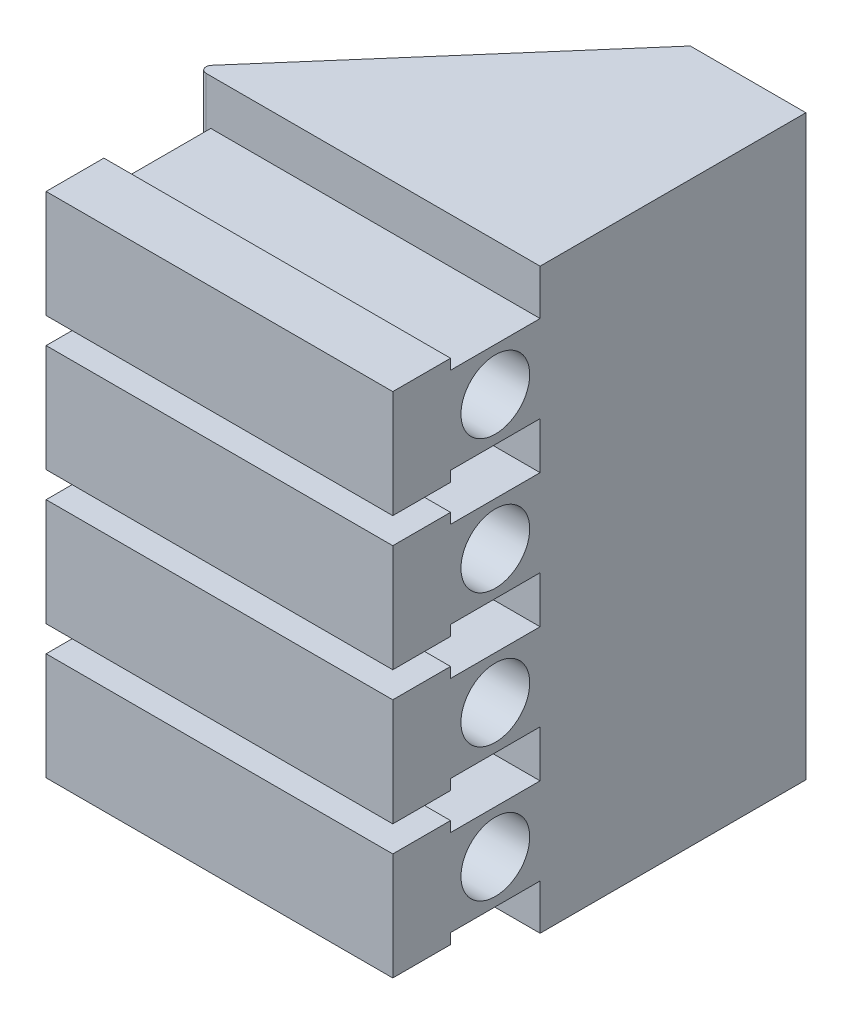
SolidWorks part; units mm, degrees
ref_plane "Front Plane" through (0, 0, 0) normal (0, 0, 1) x (1, 0, 0)
ref_plane "Top Plane" through (0, 0, 0) normal (0, 1, 0) x (1, 0, 0)
ref_plane "Right Plane" through (0, 0, 0) normal (1, 0, 0) x (0, 0, -1)
sketch "Sketch1" plane through (0, 0, 0) normal (0, 1, 0) x (1, 0, 0)
  line L0 (-17.3516, 20.3127) -> (-57.3516, -25.689)
  line L1 (-17.3516, 20.3127) -> (2.6484, 20.3127)
  line L2 (-17.3516, 20.3127) -> (-17.3516, -25.689)
  line L3 (-17.3516, -25.689) -> (2.6484, -25.689)
  line L4 (2.6484, 20.3127) -> (2.6484, -25.689)
  line L5 (-57.3516, -25.689) -> (-17.3516, -25.689)
  dimension "D1" = 20
  dimension "D2" = 40
extrude "Boss-Extrude1" add sketch "Sketch1" against normal blind 100 contours L0 L5 L2 | L4 L1 L2 L3
sketch "Sketch8" plane through (2.6484, 0, 0) normal (1, 0, 0) x (0, 0, -1)
  line L0 (-25.689, -100) -> (-25.689, 0) construction
  line L1 (-25.689, -7.85) -> (-41.189, -7.85)
  line L2 (-25.689, -7.85) -> (-25.689, -22.85)
  line L3 (-25.689, -22.85) -> (-41.189, -22.85)
  line L4 (-41.189, -7.85) -> (-41.189, -22.85)
  line L6 (-25.689, -30.95) -> (-41.189, -30.95)
  line L7 (-25.689, -30.95) -> (-25.689, -45.95)
  line L8 (-25.689, -45.95) -> (-41.189, -45.95)
  line L9 (-41.189, -30.95) -> (-41.189, -45.95)
  line L10 (-25.689, -54.05) -> (-41.189, -54.05)
  line L11 (-25.689, -54.05) -> (-25.689, -69.05)
  line L12 (-25.689, -69.05) -> (-41.189, -69.05)
  line L13 (-41.189, -54.05) -> (-41.189, -69.05)
  line L14 (-25.689, -77.15) -> (-41.189, -77.15)
  line L15 (-25.689, -77.15) -> (-25.689, -92.15)
  line L16 (-25.689, -92.15) -> (-41.189, -92.15)
  line L17 (-41.189, -77.15) -> (-41.189, -92.15)
  dimension "D1" = 7.85
  dimension "D2" = 15
  dimension "D3" = 15.5
  dimension "D4" = 8.1
  dimension "D5" = 8.1
  dimension "D6" = 8.1
  dimension "D7" = 7.85
  dimension "D8" = 15
  dimension "D9" = 15
  dimension "D10" = 15.5
  dimension "D11" = 15.5
  dimension "D12" = 15.5
extrude "Boss-Extrude2" add sketch "Sketch8" against normal blind 57
sketch "Sketch10" plane through (2.6484, 0, 0) normal (1, 0, 0) x (0, 0, -1)
  line L0 (-41.189, -7.85) -> (-41.189, -22.85) construction
  line L1 (-41.189, -22.85) -> (-25.689, -22.85) construction
  line L2 (-41.189, -30.95) -> (-41.189, -45.95) construction
  line L3 (-41.189, -45.95) -> (-25.689, -45.95) construction
  line L4 (-41.189, -54.05) -> (-41.189, -69.05) construction
  line L5 (-41.189, -69.05) -> (-25.689, -69.05) construction
  line L6 (-41.189, -77.15) -> (-41.189, -92.15) construction
  line L7 (-41.189, -92.15) -> (-25.689, -92.15) construction
  circle A0 centre (-33.439, -15.35) radius 5.95
  circle A1 centre (-33.439, -38.45) radius 5.95
  circle A2 centre (-33.439, -61.55) radius 5.95
  circle A3 centre (-33.439, -84.65) radius 5.95
  dimension "D1" = 11.9
  dimension "D2" = 11.9
  dimension "11.9" = 11.9
  dimension "D4" = 11.9
  dimension "D5" = 7.75
  dimension "D6" = 7.5
  dimension "D7" = 7.75
  dimension "D8" = 7.5
  dimension "D9" = 7.75
  dimension "D10" = 7.5
  dimension "D11" = 7.75
  dimension "D12" = 7.5
extrude "Cut-Extrude1" cut sketch "Sketch10" against normal blind 51
sketch "Sketch11" plane through (2.6484, 0, 0) normal (1, 0, 0) x (0, 0, -1)
  line L1 (-41.189, -6.05) -> (-51.189, -6.05)
  line L2 (-41.189, -6.05) -> (-41.189, -24.65)
  line L3 (-41.189, -24.65) -> (-51.189, -24.65)
  line L4 (-51.189, -6.05) -> (-51.189, -24.65)
  line L5 (-25.689, -7.85) -> (-41.189, -7.85) construction
  line L6 (-25.689, -26.9) -> (20.3127, -26.9) construction
  line L7 (-25.689, -30.95) -> (-25.689, -22.85) construction
  line L8 (20.3127, -100) -> (20.3127, 0) construction
  line L9 (-25.689, -50) -> (20.3127, -50) construction
  line L10 (-25.689, -54.05) -> (-25.689, -45.95) construction
  line L11 (-41.189, -29.15) -> (-51.189, -29.15)
  line L12 (-51.189, -47.75) -> (-51.189, -29.15)
  line L13 (-41.189, -47.75) -> (-51.189, -47.75)
  line L14 (-41.189, -47.75) -> (-41.189, -29.15)
  line L15 (-41.189, -75.35) -> (-51.189, -75.35)
  line L16 (-51.189, -93.95) -> (-51.189, -75.35)
  line L17 (-41.189, -93.95) -> (-51.189, -93.95)
  line L18 (-41.189, -93.95) -> (-41.189, -75.35)
  line L19 (-41.189, -52.25) -> (-41.189, -70.85)
  line L20 (-41.189, -52.25) -> (-51.189, -52.25)
  line L21 (-51.189, -52.25) -> (-51.189, -70.85)
  line L22 (-41.189, -70.85) -> (-51.189, -70.85)
  dimension "D1" = 10
  dimension "D2" = 18.6
  dimension "D3" = 1.8
extrude "Boss-Extrude3" add sketch "Sketch11" against normal blind 60
fillet "Fillet2" radius 1 1 edges at (-57.3516, -50, 25.689)
